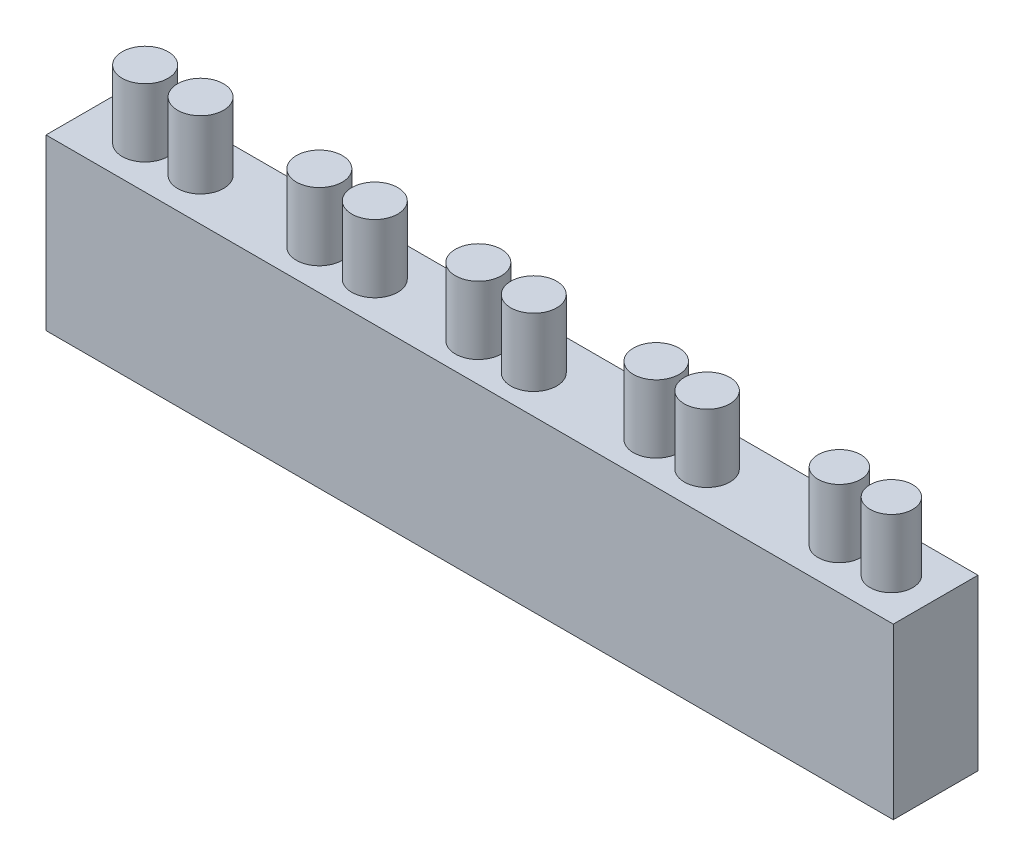
SolidWorks part; units mm, degrees
ref_plane "Front Plane" through (0, 0, 0) normal (0, 0, 1) x (1, 0, 0)
ref_plane "Top Plane" through (0, 0, 0) normal (0, 1, 0) x (1, 0, 0)
ref_plane "Right Plane" through (0, 0, 0) normal (1, 0, 0) x (0, 0, -1)
sketch "Sketch1" plane through (0, 0, 0) normal (0, 1, 0) x (1, 0, 0)
  line L1 (50, -5) -> (-50, -5)
  line L2 (50, -5) -> (50, 5)
  line L3 (50, 5) -> (-50, 5)
  line L4 (-50, -5) -> (-50, 5)
  line L5 (50, -5) -> (-50, 5) construction
  line L6 (50, 5) -> (-50, -5) construction
  point P0 (0, 0)
  dimension "D1" = 100
  dimension "1cm" = 10
extrude "Boss-Extrude1" add sketch "Sketch1" along normal blind 20
sketch "Sketch2" plane through (0, 20, 0) normal (0, 1, 0) x (1, 0, 0)
  circle A0 centre (-43.2986, 0) radius 2.7132
  circle A1 centre (-36.7581, 0) radius 2.7132
  circle A2 centre (-22.4081, -0.3284) radius 2.7132
  circle A3 centre (-15.8676, -0.3284) radius 2.7132
  circle A4 centre (17.14, -0.119) radius 2.6942
  circle A5 centre (23.1469, -0.119) radius 2.6942
  circle A6 centre (38.7616, -0.119) radius 2.5238
  circle A7 centre (44.8984, -0.119) radius 2.5238
  circle A8 centre (-3.447, -0.525) radius 2.7132
  circle A9 centre (3.0935, -0.525) radius 2.7132
extrude "Boss-Extrude2" add sketch "Sketch2" along normal blind 8
